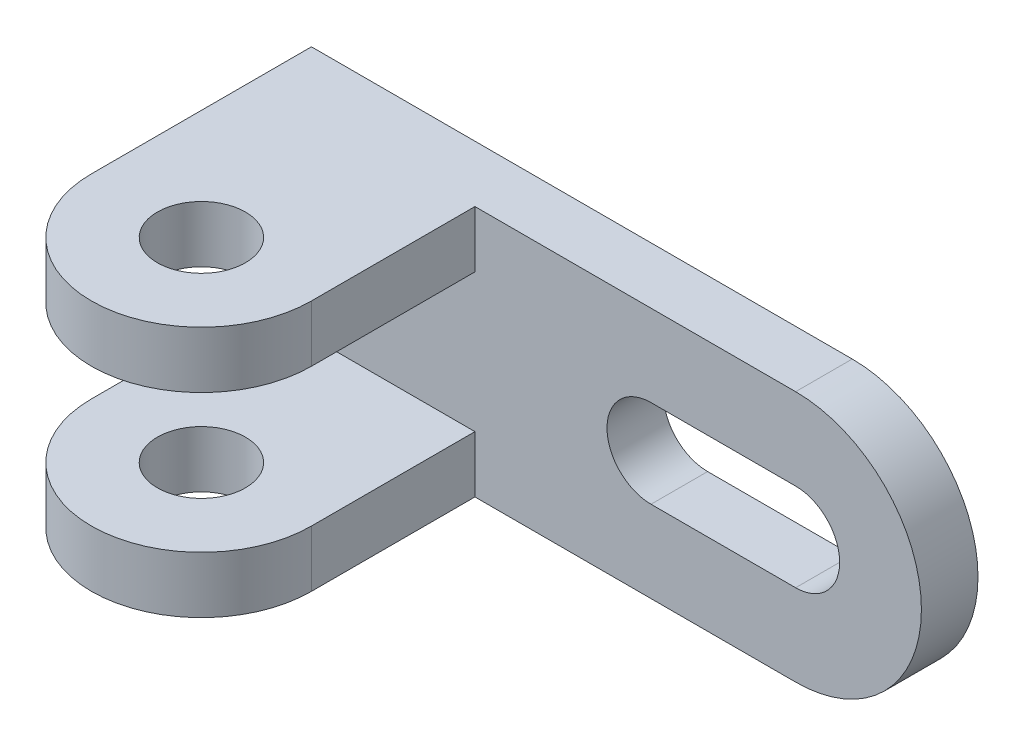
SolidWorks part; units mm, degrees
ref_plane "Płaszczyzna przednia" through (0, 0, 0) normal (0, 0, 1) x (1, 0, 0)
ref_plane "Płaszczyzna górna" through (0, 0, 0) normal (0, 1, 0) x (1, 0, 0)
ref_plane "Płaszczyzna prawa" through (0, 0, 0) normal (1, 0, 0) x (0, 0, -1)
sketch "Szkic1" plane through (0, 0, 0) normal (0, 0, 1) x (1, 0, 0)
  line L0 (-23, 7) -> (0, 7)
  line L1 (-23, -7) -> (0, -7)
  line L2 (-86, 20) -> (-86, -20)
  line L3 (0, 20) -> (-86, 20)
  line L4 (-86, -20) -> (0, -20)
  circle A0 centre (0, 0) radius 7
  circle A1 centre (-23, 0) radius 7
  arc A2 (0, -20) -> (0, 20) centre (0, 0) ccw
  dimension "D1" = 14
  dimension "D4" = 20
  dimension "D2" = 23
  dimension "D3" = 86
extrude "Dodanie-wyciągnięcie1" add sketch "Szkic1" along normal blind 9 contours L4 A2 L3 L2 A1 L0 A0 L1
sketch "Szkic3" plane through (0, -20, 0) normal (0, -1, 0) x (1, 0, 0)
  line L0 (-86, 0) -> (-86, 35)
  line L1 (-86, 0) -> (0, 0) construction
  line L2 (-51, 0) -> (-51, 35)
  line L3 (-86, 0) -> (-51, 0)
  circle A0 centre (-68.5, 35) radius 17.5
  circle A1 centre (-68.5, 35) radius 7
  line M6 (0, 9) -> (-86, 9)
  dimension "D1" = 35
  dimension "D3" = 14
  dimension "D2" = 35
extrude "Dodanie-wyciągnięcie2" add sketch "Szkic3" against normal blind 9 contours A0 A1 | A0 L0 L2 M6
sketch "Szkic4" plane through (0, 20, 0) normal (0, 1, 0) x (1, 0, 0)
  line L0 (-86, 0) -> (-86, -35)
  line L1 (-51, 0) -> (-51, -35)
  line L2 (0, 0) -> (-86, 0) construction
  line L3 (-86, 0) -> (-51, 0)
  circle A0 centre (-68.5, -35) radius 17.5
  circle A1 centre (-68.5, -35) radius 7
  dimension "D1" = 35
  dimension "D3" = 14
  dimension "D2" = 35
extrude "Dodanie-wyciągnięcie3" add sketch "Szkic4" against normal blind 9
